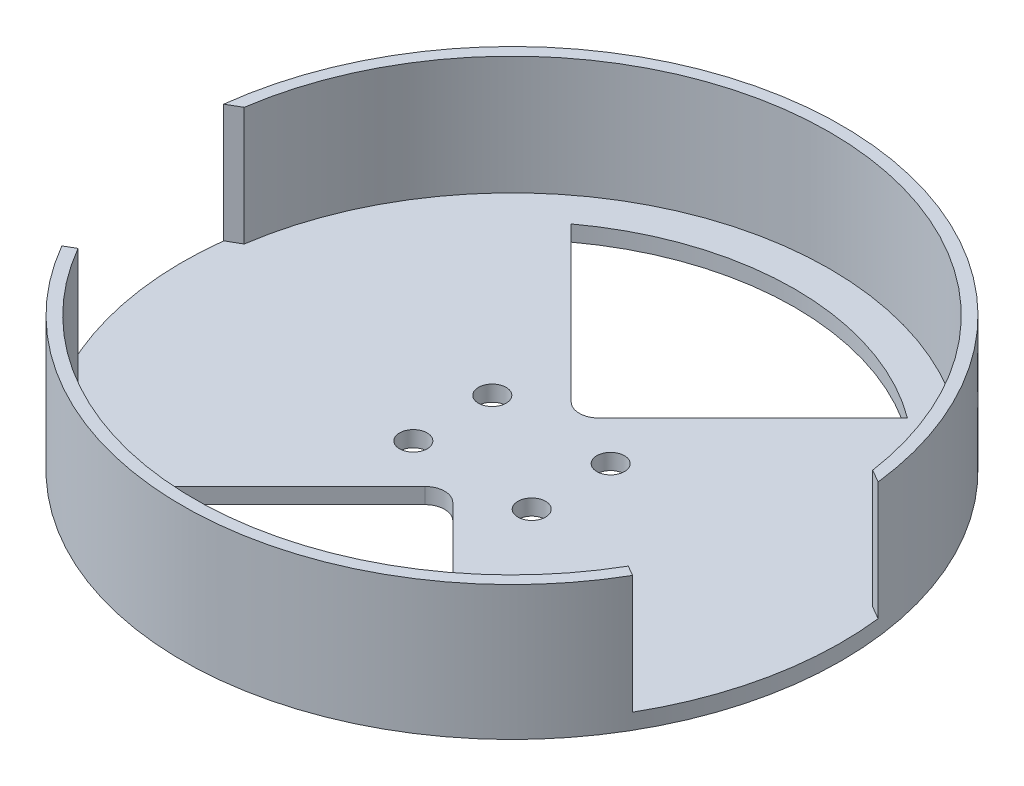
SolidWorks part; units mm, degrees
ref_plane "Alzado" through (0, 0, 0) normal (0, 0, 1) x (1, 0, 0)
ref_plane "Planta" through (0, 0, 0) normal (0, 1, 0) x (1, 0, 0)
ref_plane "Vista lateral" through (0, 0, 0) normal (1, 0, 0) x (0, 0, -1)
sketch "Croquis1" plane through (0, 0, 0) normal (0, 1, 0) x (1, 0, 0)
  circle A1 centre (0, 0) radius 80.5
extrude "Saliente-Extruir1" add sketch "Croquis1" along normal blind 4
sketch "Croquis2" plane through (0, 0, 0) normal (0, 1, 0) x (1, 0, 0)
  circle A0 centre (0, 0) radius 80.5
extrude "Extruir-Lámina1" add sketch "Croquis2" along normal blind 34 thin
sketch "Croquis3" plane through (0, 34, 0) normal (0, 1, 0) x (1, 0, 0)
  line L0 (0, 0) -> (0, 83.5)
  line L1 (0, 0) -> (93.3497, -53.8955)
  line L2 (0, 0) -> (-98.2747, -56.7389)
  line L3 (-98.2747, -56.7389) -> (0, 0)
  line L4 (-72.3131, -41.75) -> (-97.3131, 1.5513)
  line L5 (-97.3131, 1.5513) -> (-79.6369, 11.7567)
  line L6 (-79.6369, 11.7567) -> (-54.6369, -31.5446)
  line L7 (72.3131, -41.75) -> (97.3131, 1.5513)
  line L8 (97.3131, 1.5513) -> (79.6369, 11.7567)
  line L9 (79.6369, 11.7567) -> (54.6369, -31.5446)
  circle A0 centre (0, 0) radius 83.5 construction
  circle A1 centre (0, 0) radius 80.5 construction
  circle A2 centre (0, 0) radius 80.5 construction
  circle M4 centre (0, 0) radius 83.5
  circle M5 centre (0, 0) radius 80.5
  dimension "D1" = 120
  dimension "D2" = 120
extrude "Cortar-Extruir1" cut sketch "Croquis3" against normal up to surface (30 mm away) contours L8 L1 M4 M5 | L5 L2 M4 M5 up to face at (0, 4, 80.5)
sketch "Croquis4" plane through (0, 0, 0) normal (0, -1, 0) x (1, 0, 0)
  line L0 (0, 0) -> (0, 15)
  line L1 (-3.5355, 18.5355) -> (-42.6034, 57.6034)
  line L2 (3.5355, 18.5355) -> (42.6034, 57.6034)
  line L3 (3.5355, -18.5355) -> (42.6034, -57.6034)
  line L4 (-3.5355, -18.5355) -> (-42.6034, -57.6034)
  circle A0 centre (0, 0) radius 71.6463
  arc A1 (3.5355, 18.5355) -> (-3.5355, 18.5355) centre (0, 22.0711) cw
  arc A2 (-3.5355, -18.5355) -> (3.5355, -18.5355) centre (0, -22.0711) cw
  dimension "D1" = 5
extrude "Cortar-Extruir3" cut sketch "Croquis4" against normal up to surface (4 mm away) contours A1 L2 A0 L1 | A2 L4 A0 L3 up to face at (0, 4, 11.7478)
sketch "Croquis6" plane through (0, 0, 0) normal (0, -1, 0) x (1, 0, 0)
  line L0 (0, 0) -> (15, 0)
  line L1 (15, 0) -> (15, 10)
  line L2 (15, 10) -> (15, -10)
  line L3 (0, 0) -> (-15, 0)
  line L4 (-15, 0) -> (-15, 10)
  line L5 (-15, 10) -> (-15, -10)
  circle A0 centre (-15, 10) radius 3.5
  circle A1 centre (-15, -10) radius 3.5
  circle A2 centre (15, 10) radius 3.5
  circle A3 centre (15, -10) radius 3.5
extrude "Cortar-Extruir4" cut sketch "Croquis6" against normal blind 10
